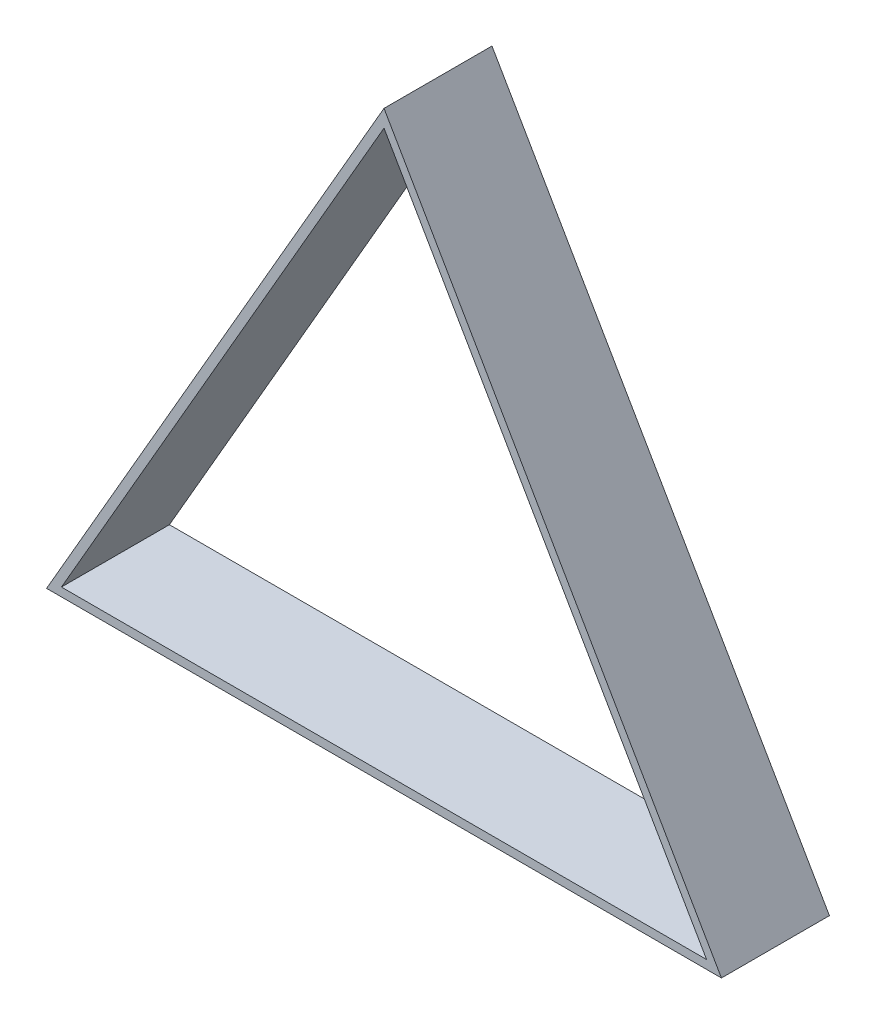
SolidWorks part; units mm, degrees
ref_plane "Front Plane" through (0, 0, 0) normal (0, 0, 1) x (1, 0, 0)
ref_plane "Top Plane" through (0, 0, 0) normal (0, 1, 0) x (1, 0, 0)
ref_plane "Right Plane" through (0, 0, 0) normal (1, 0, 0) x (0, 0, -1)
sketch "Sketch2" plane through (0, 0, 0) normal (0, 0, 1) x (1, 0, 0)
  line L0 (0, 0) -> (125, 216.5064)
  line L1 (125, 216.5064) -> (250, 0)
  line L2 (250, 0) -> (0, 0)
  line L3 (125, 210.1564) -> (5.4993, 3.175)
  line L4 (5.4993, 3.175) -> (244.5007, 3.175)
  line L5 (244.5007, 3.175) -> (125, 210.1564)
  dimension "D1" = 60
  dimension "D2" = 60
  dimension "D3" = 250
  dimension "D4" = 3.175
  dimension "D5" = 3.175
  dimension "D6" = 3.175
extrude "Boss-Extrude2" add sketch "Sketch2" along normal blind 40
sketch "Sketch3" plane through (0, 0, 0) normal (0, 0, 1) x (1, 0, 0)
  circle A0 centre (125, 72.1688) radius 144.3376
